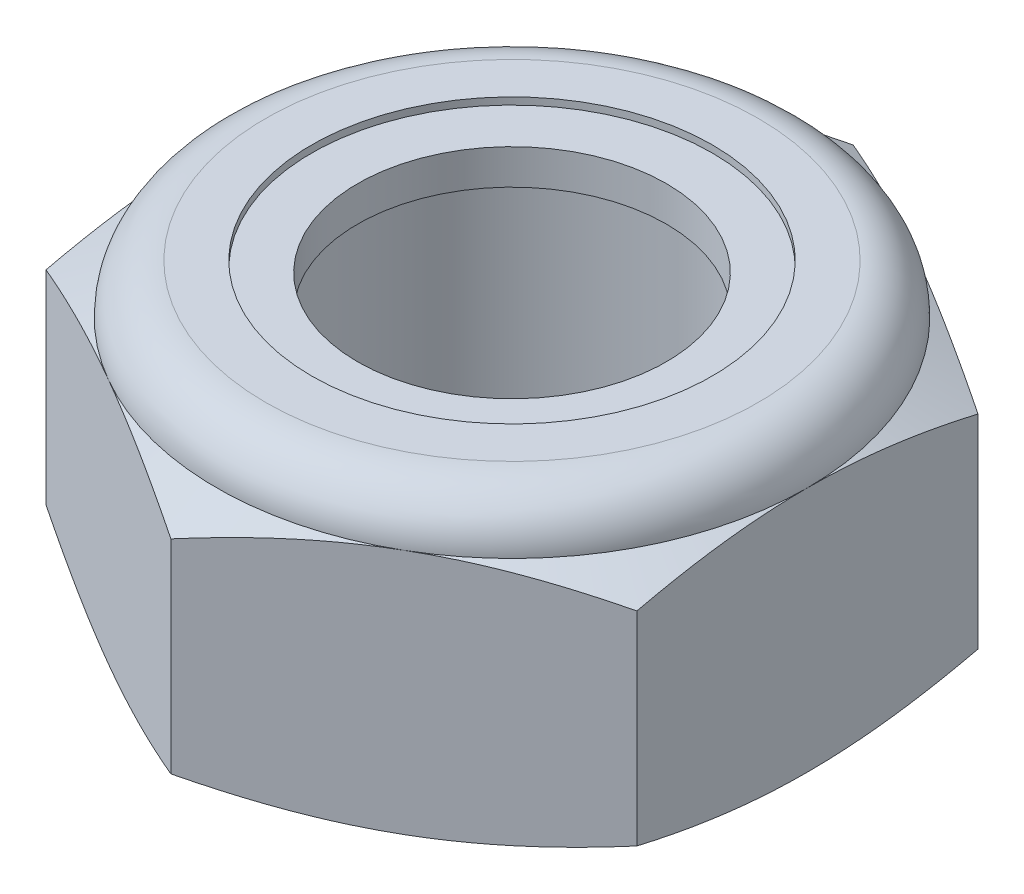
SolidWorks part; units mm, degrees
material "Plain Carbon Steel"
ref_plane "Front" through (0, 0, 0) normal (0, 0, 1) x (1, 0, 0)
ref_plane "Top" through (0, 0, 0) normal (0, 1, 0) x (1, 0, 0)
ref_plane "Right" through (0, 0, 0) normal (1, 0, 0) x (0, 0, -1)
sketch "Sketch1" plane through (0, 0, 0) normal (0, 1, 0) x (1, 0, 0)
  line L1 (0, 7.3323) -> (-6.35, 3.6662)
  line L2 (-6.35, 3.6662) -> (-6.35, -3.6662)
  line L3 (-6.35, -3.6662) -> (0, -7.3323)
  line L4 (0, -7.3323) -> (6.35, -3.6662)
  line L5 (6.35, -3.6662) -> (6.35, 3.6662)
  line L6 (6.35, 3.6662) -> (0, 7.3323)
  circle A0 centre (0, 0) radius 6.35 construction
  dimension "Hex Flats" = 12.7
extrude "Extrude1" add sketch "Sketch1" along normal blind 6.35
sketch "Sketch2" plane through (0, 0, 0) normal (1, 0, 0) x (0, 0, -1)
  line L0 (-3.9624, 0) -> (-3.9624, 6.35) construction
  line L1 (0, 0) -> (3.9624, 0)
  line L2 (0, 0) -> (0, 6.35)
  line L3 (0, 6.35) -> (3.9624, 6.35)
  line L4 (3.9624, 0) -> (3.9624, 6.35)
  line L5 (-3.6662, 6.35) -> (3.6662, 6.35) construction
  line L7 (0, -3.9624) -> (0, 0) construction
  dimension "Thread Dia" = 7.9248
revolve "Revolve1" add sketch "Sketch2" angle 360 about L7
sketch "Sketch3" plane through (0, 0, 0) normal (1, 0, 0) x (0, 0, -1)
  line L0 (3.9624, 6.35) -> (-3.9624, 6.35) construction
  line L1 (-3.9624, 6.35) -> (-3.9624, 4.9389) construction
  line L2 (-3.9624, 4.9389) -> (3.9624, 6.35) construction
  line L3 (3.9624, 6.35) -> (3.9933, 6.1763) construction
  line L4 (3.9933, 6.1763) -> (4.2098, 4.9607)
  line L5 (4.2098, 4.9607) -> (3.3805, 5.261)
  line L6 (3.3805, 5.261) -> (3.3187, 5.6083)
  line L7 (3.3187, 5.6083) -> (3.9933, 6.1763)
  line L8 (3.3496, 5.4346) -> (4.1015, 5.5685) construction
  line L9 (3.9624, 6.35) -> (3.9624, 5.5438) construction
  line L10 (3.9624, 5.5438) -> (-3.9624, 4.1327) construction
  line L11 (-3.9624, 4.1327) -> (-3.9624, 4.9389) construction
  line L12 (-0.2692, 6.35) -> (0.2692, 3.3264) construction
  line L13 (-3.9624, 0) -> (-3.9624, 6.35) construction
  line L14 (0, 6.35) -> (3.9624, 6.35) construction
  line L15 (3.9624, 0) -> (3.9624, 6.35) construction
  point P13 (0, 4.8382)
  dimension "D1" = 0.1764
  dimension "D2" = 0.3528
  dimension "Thread Pitch" = 1.4111
  dimension "D4" = 60
  dimension "D5" = 1.4111
sketch "Sketch4" plane through (0, 0, 0) normal (1, 0, 0) x (0, 0, -1)
  line L0 (0, 6.35) -> (3.9624, 6.35)
  line L1 (3.9624, 6.35) -> (3.3187, 6.0498)
  line L2 (3.3187, 6.0498) -> (3.3187, 0.3002)
  line L3 (3.3187, 0.3002) -> (3.9624, 0)
  line L4 (3.9624, 0) -> (0, 0)
  line L5 (0, 0) -> (0, 6.35)
  line L6 (3.9624, 0) -> (3.9624, 6.35) construction
  line L7 (0, 6.35) -> (3.9624, 6.35) construction
  line L8 (0, 0) -> (3.9624, 0) construction
  line L9 (0, 0) -> (0, 6.35) construction
  line L10 (0, 6.35) -> (0, 7.0603) construction
  dimension "D1" = 25
combine bodies "Combine1" operation type subtract main body 108 bodies to subtract 109
sketch "Sketch5" plane through (0, 0, 0) normal (1, 0, 0) x (0, 0, -1)
  line L0 (0, 0) -> (6.35, 0)
  line L1 (6.35, 0) -> (7.3323, 0.4581)
  line L2 (7.3323, 0.4581) -> (7.3323, 4.8336)
  line L3 (7.3323, 4.8336) -> (6.35, 5.2917)
  line L4 (5.2917, 6.35) -> (5.2917, 7.62)
  line L5 (5.2917, 7.62) -> (8.6023, 7.62)
  line L6 (8.6023, 7.62) -> (8.6023, -1.27)
  line L7 (8.6023, -1.27) -> (0, -1.27)
  line L8 (0, -1.27) -> (0, 0)
  line L9 (6.35, 5.2917) -> (6.35, 0) construction
  line L10 (0, 0) -> (3.9624, 0) construction
  line L13 (7.3323, 2.6458) -> (8.6023, 2.6458) construction
  line L14 (7.3323, 6.35) -> (7.3323, 0) construction
  line L15 (0, 0) -> (0, 7.62) construction
  line L20 (0, 7.62) -> (5.2917, 7.62) construction
  line L22 (0, 6.35) -> (3.9624, 6.35) construction
  arc A0 (6.35, 5.2917) -> (5.2917, 6.35) centre (5.2917, 5.2917) ccw
  dimension "D1" = 25
  dimension "D2" = 1.27
  dimension "D3" = 6.35
  dimension "D4" = 1.0583
revolve "Cut-Revolve3" cut sketch "Sketch5" angle 360 about L15
sketch "Sketch6" plane through (0, 0, 0) normal (1, 0, 0) x (0, 0, -1)
  line L0 (0, 5.2917) -> (6.1976, 5.2917)
  line L1 (5.2917, 6.1976) -> (4.3052, 6.1976)
  line L2 (0, 7.62) -> (0, 5.2917)
  line L3 (4.3052, 7.62) -> (0, 7.62)
  line L4 (0, 7.62) -> (5.2917, 7.62) construction
  line L5 (0, 0) -> (0, 7.62) construction
  line L6 (0, 7.62) -> (0, 44.323) construction
  line L7 (4.3052, 6.1976) -> (4.3052, 7.62)
  line L8 (5.2917, 6.35) -> (5.2917, 6.1976) construction
  line L9 (4.3052, 6.1976) -> (3.3187, 6.1976) construction
  line L10 (3.3187, 6.1976) -> (3.3187, 6.0498) construction
  arc A0 (6.1976, 5.2917) -> (5.2917, 6.1976) centre (5.2917, 5.2917) ccw
  arc A1 (6.35, 5.2917) -> (5.2917, 6.35) centre (5.2917, 5.2917) ccw construction
  dimension "D1" = 0.1524
revolve "Cut-Revolve4" cut sketch "Sketch6" angle 360 about L6
sketch "Sketch7" plane through (0, 0, 0) normal (1, 0, 0) x (0, 0, -1)
  line L0 (3.3187, 5.3679) -> (6.1179, 5.3679)
  line L1 (5.2917, 6.1214) -> (3.3187, 6.1214)
  line L2 (3.3187, 6.1214) -> (3.3187, 5.3679)
  line L3 (3.3187, 5.3679) -> (0, 5.3679) construction
  line L4 (0, 5.3679) -> (0, 6.1214) construction
  line L5 (0, 6.1214) -> (3.3187, 6.1214) construction
  line L6 (3.3187, 5.3679) -> (3.3187, 5.2917) construction
  line L7 (0, 5.2917) -> (6.1976, 5.2917) construction
  line L8 (5.2917, 6.1214) -> (5.2917, 6.1976) construction
  arc A0 (6.1179, 5.3679) -> (5.2917, 6.1214) centre (5.2917, 5.2917) ccw
  arc A2 (6.1976, 5.2917) -> (5.2917, 6.1976) centre (5.2917, 5.2917) ccw construction
  dimension "D1" = 0.0762
revolve "Revolve2" add sketch "Sketch7" angle 360 about L4
equation "\"D1@Sketch3\"=\"Thread Pitch@Sketch3\"/8"
equation "\"D2@Sketch3\"=\"Thread Pitch@Sketch3\"/4"
equation "\"D5@Sketch3\"=\"Thread Pitch@Sketch3\""
equation "\"D4@Sketch5\"=\"Height@Extrude1\"/6"
